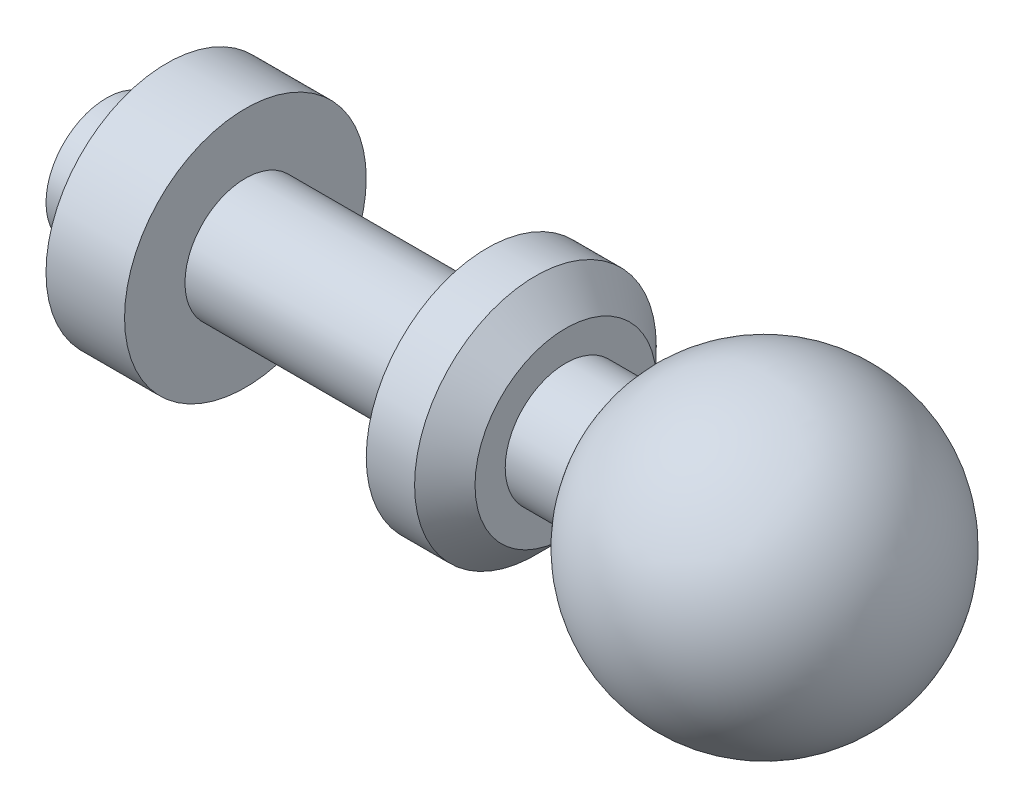
SolidWorks part; units mm, degrees
ref_plane "Front Plane" through (0, 0, 0) normal (0, 0, 1) x (1, 0, 0)
ref_plane "Top Plane" through (0, 0, 0) normal (0, 1, 0) x (1, 0, 0)
ref_plane "Right Plane" through (0, 0, 0) normal (1, 0, 0) x (0, 0, -1)
sketch "Sketch1" plane through (0, 0, 0) normal (0, 0, 1) x (1, 0, 0)
  line L0 (0, 0) -> (0, 10)
  line L1 (0, 10) -> (10, 10)
  line L2 (10, 10) -> (10, 20)
  line L3 (10, 20) -> (23, 20)
  line L4 (23, 20) -> (23, 10)
  line L5 (23, 10) -> (63, 10)
  line L6 (63, 10) -> (63, 20)
  line L7 (63, 20) -> (71, 20)
  line L8 (76, 15) -> (76, 10)
  line L9 (76, 10) -> (86, 10)
  line L10 (0, 0) -> (133.9129, 0)
  line L11 (0, 0) -> (215.2528, 0) construction
  line L12 (71, 20) -> (76, 15)
  arc A0 (133.9129, 0) -> (86, 10) centre (108.9129, 0) ccw
  point P9 (76, 20)
  dimension "D7" = 25
  dimension "D8" = 13
  dimension "D1" = 10
  dimension "D2" = 13
  dimension "D3" = 20
  dimension "D4" = 10
  dimension "D5" = 40
  dimension "D6" = 10
revolve "Revolve1" add sketch "Sketch1" angle 360 about L11
